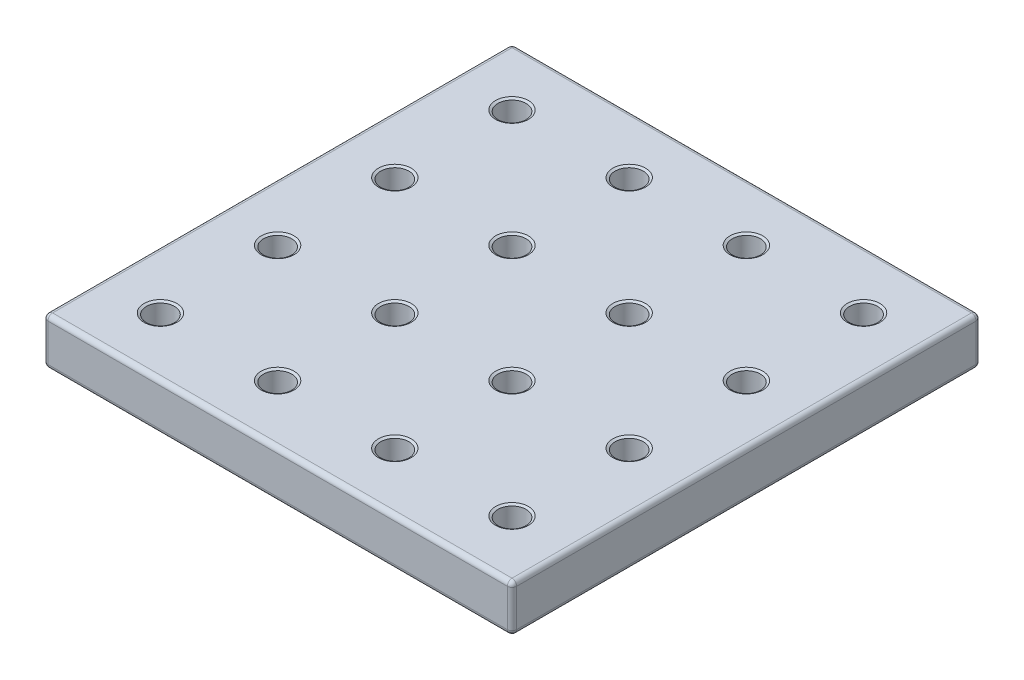
SolidWorks part; units mm, degrees
ref_plane "Front Plane" through (0, 0, 0) normal (0, 0, 1) x (1, 0, 0)
ref_plane "Top Plane" through (0, 0, 0) normal (0, 1, 0) x (1, 0, 0)
ref_plane "Right Plane" through (0, 0, 0) normal (1, 0, 0) x (0, 0, -1)
sketch "Base Sketch" plane through (0, 0, 0) normal (0, 1, 0) x (1, 0, 0)
  line L1 (-25, 25) -> (25, 25)
  line L2 (-25, 25) -> (-25, -25)
  line L3 (-25, -25) -> (25, -25)
  line L4 (25, 25) -> (25, -25)
  line L5 (-25, 25) -> (25, -25) construction
  line L6 (-25, -25) -> (25, 25) construction
  point P0 (0, 0)
  dimension "D1" = 50
extrude "Base Extrude" add sketch "Base Sketch" along normal blind 5
sketch "Circles Sketch" plane through (0, 5, 0) normal (0, 1, 0) x (1, 0, 0)
  line L0 (-18.75, 6.25) -> (-6.25, 6.25) construction
  line L2 (-6.25, 6.25) -> (6.25, 6.25) construction
  line L3 (6.25, 6.25) -> (18.75, 6.25) construction
  line L4 (-18.75, -6.25) -> (-6.25, -6.25) construction
  line L5 (-6.25, -6.25) -> (6.25, -6.25) construction
  line L7 (6.25, -6.25) -> (18.75, -6.25) construction
  line L10 (-18.75, 18.75) -> (-18.75, -18.75) construction
  line L12 (-6.25, 18.75) -> (-6.25, -18.75) construction
  line L13 (6.25, 18.75) -> (6.25, -18.75) construction
  line L14 (18.75, 18.75) -> (18.75, -18.75) construction
  line L15 (-18.75, 18.75) -> (18.75, 18.75) construction
  line L17 (-18.75, 6.25) -> (18.75, 6.25) construction
  line L18 (-18.75, -6.25) -> (18.75, -6.25) construction
  line L19 (-18.75, -18.75) -> (18.75, -18.75) construction
  circle A0 centre (-18.75, 18.75) radius 1.5
  circle A1 centre (-6.25, 18.75) radius 1.5
  circle A2 centre (6.25, 18.75) radius 1.5
  circle A3 centre (18.75, 18.75) radius 1.5
  circle A4 centre (-18.75, 6.25) radius 1.5
  circle A5 centre (-6.25, 6.25) radius 1.5
  circle A6 centre (6.25, 6.25) radius 1.5
  circle A7 centre (18.75, 6.25) radius 1.5
  circle A8 centre (-18.75, -6.25) radius 1.5
  circle A9 centre (-6.25, -6.25) radius 1.5
  circle A10 centre (6.25, -6.25) radius 1.5
  circle A11 centre (18.75, -6.25) radius 1.5
  circle A12 centre (-18.75, -18.75) radius 1.5
  circle A13 centre (-6.25, -18.75) radius 1.5
  circle A14 centre (6.25, -18.75) radius 1.5
  circle A15 centre (18.75, -18.75) radius 1.5
extrude "Circle Cuts" cut sketch "Circles Sketch" against normal blind 5 contours A7 | A3 | A2 | A6 | A10 | A9 | A5 | A1 | A0 | A4 | A8 | A15 | A11 | A14 | A13 | A12
fillet "Edge Fillet" radius 0.5 12 edges at (-25, 2.5, -25) (-25, 2.5, 25) (25, 2.5, 25) (25, 2.5, -25) (0, 0, -25) (0, 0, 25) (-25, 0, 0) (0, 5, 25) (-25, 5, 0) (0, 5, -25) (25, 0, 0) (25, 5, 0)
chamfer "Circular Chamfer" distance 0.25 angle 30 32 edges at (18.75, 5, -17.25) (18.75, 5, -4.75) (18.75, 5, 7.75) (18.75, 5, 20.25) (6.25, 5, -17.25) (6.25, 5, -4.75) (6.25, 5, 7.75) (6.25, 5, 20.25) (-6.25, 5, -17.25) (-6.25, 5, -4.75) (-6.25, 5, 7.75) (-6.25, 5, 20.25) (-18.75, 5, -17.25) (-18.75, 5, -4.75) (-18.75, 5, 7.75) (-18.75, 5, 20.25) (18.75, 0, 20.25) (18.75, 0, 7.75) (18.75, 0, -4.75) (18.75, 0, -17.25) (6.25, 0, 20.25) (6.25, 0, 7.75) (6.25, 0, -4.75) (6.25, 0, -17.25) (-6.25, 0, 20.25) (-6.25, 0, 7.75) (-6.25, 0, -4.75) (-6.25, 0, -17.25) (-18.75, 0, 20.25) (-18.75, 0, 7.75) (-18.75, 0, -4.75) (-18.75, 0, -17.25)
